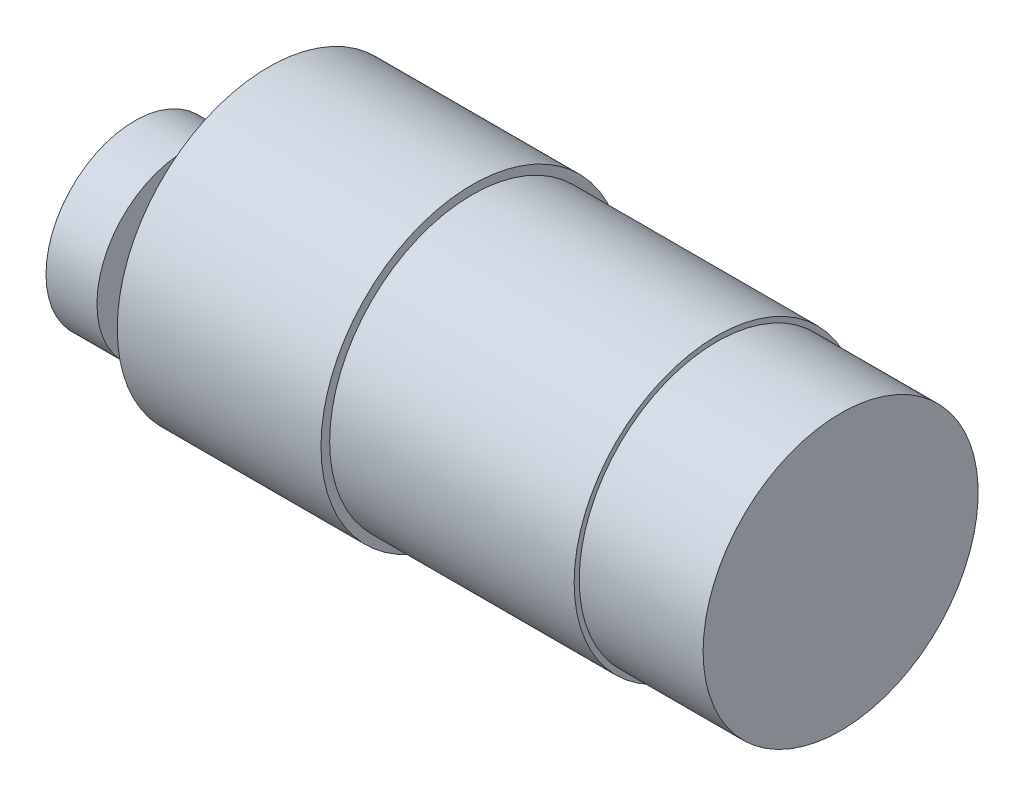
SolidWorks part; units mm, degrees
ref_plane "Face" through (0, 0, 0) normal (0, 0, 1) x (1, 0, 0)
ref_plane "Dessus" through (0, 0, 0) normal (0, 1, 0) x (1, 0, 0)
ref_plane "Droite" through (0, 0, 0) normal (1, 0, 0) x (0, 0, -1)
sketch "Esquisse6" plane through (0, 0, 0) normal (1, 0, 0) x (0, 0, -1)
  circle A0 centre (0, 0) radius 18.8595
  dimension "D1" = 37.719
extrude "Boss.-Extru.2" add sketch "Esquisse6" along normal blind 25.4
sketch "Esquisse7" plane through (25.4, 0, 0) normal (1, 0, 0) x (0, 0, -1)
  circle A0 centre (0, 0) radius 17.78
  dimension "D1" = 35.56
extrude "Boss.-Extru.3" add sketch "Esquisse7" along normal blind 30.48
sketch "Esquisse8" plane through (55.88, 0, 0) normal (1, 0, 0) x (0, 0, -1)
  circle A0 centre (0, 0) radius 17.145
  dimension "D1" = 34.29
extrude "Boss.-Extru.4" add sketch "Esquisse8" along normal blind 15.4432
sketch "Esquisse9" plane through (0, 0, 0) normal (-1, 0, 0) x (0, 0, 1)
  circle A0 centre (0, -6.35) radius 5.969
  dimension "D1" = 11.938
  dimension "D2" = 6.35
extrude "Boss.-Extru.5" add sketch "Esquisse9" along normal blind 6.096
sketch "Esquisse10" plane through (-6.096, 0, 0) normal (-1, 0, 0) x (0, 0, 1)
  circle A0 centre (0, -6.35) radius 4.699
  circle A1 centre (0, -6.35) radius 5.969 construction
  dimension "D1" = 9.398
extrude "Boss.-Extru.6" add sketch "Esquisse10" along normal blind 4.2333
sketch "Esquisse11" plane through (-10.3293, 0, 0) normal (-1, 0, 0) x (0, 0, 1)
  circle A0 centre (0, -6.35) radius 11.0617
  circle A1 centre (0, -6.35) radius 4.699 construction
  dimension "D1" = 22.1234
extrude "Boss.-Extru.7" add sketch "Esquisse11" along normal blind 6.35
sketch "Esquisse12" plane through (-16.6793, 0, 0) normal (-1, 0, 0) x (0, 0, 1)
  circle A0 centre (0, -6.35) radius 4.7752
  circle A1 centre (0, -6.35) radius 11.0617 construction
  dimension "D1" = 9.5504
extrude "Boss.-Extru.8" add sketch "Esquisse12" along normal blind 3.302
hole_wizard "Perçage pour tuyau pour trou taraudé 1/161" positions "Esquisse13" profile "Esquisse15" hole size "1/16" standard "Ansi Inch"
sketch "Esquisse13" plane through (-19.9813, 0, 0) normal (-1, 0, 0) x (0, 0, 1)
  circle A1 centre (0, -6.35) radius 4.7752 construction
  point P0 (0, -6.35)
sketch "Esquisse15" plane through (-19.9813, -6.35, 0) normal (0, 1, 0) x (0, 0, 1)
  line L0 (0, 0) -> (0, 19.9813)
  line L1 (0, 19.9813) -> (3.0734, 19.9813)
  line L2 (3.0734, 19.9813) -> (3.0734, 0)
  line L5 (3.0734, 0) -> (0, 0)
  line L10 (0, 19.9813) -> (-3.0734, 19.9813) construction
  line L11 (0, -6.35) -> (0, 107.95) construction
  dimension "Diamètre du perçage" = 6.1468
  dimension "Profondeur du perçage" = 19.9813
  dimension "Angle de pointe" = 180
sketch "Esquisse16" plane through (0, 0, 0) normal (-1, 0, 0) x (0, 0, 1)
  line L0 (-1.778, -3.9688) -> (1.778, -3.9688)
  arc A0 (-1.778, -3.9688) -> (1.778, -3.9688) centre (0, -6.35) ccw
  point P5 (0, -3.9688)
  dimension "D1" = 5.9436
  dimension "D2" = 3.556
extrude "Boss.-Extru.9" add sketch "Esquisse16" along normal up to surface (19.9813 mm away) up to face at (-19.9813, -6.35, 3.0734)
sketch "Esquisse17" plane through (-19.9813, 0, 0) normal (-1, 0, 0) x (0, 0, 1)
  line L0 (-1.778, -3.9688) -> (1.778, -3.9688)
  arc A3 (-1.778, -3.9688) -> (1.778, -3.9688) centre (0, -6.35) ccw
extrude "Boss.-Extru.10" add sketch "Esquisse17" along normal blind 2.032
sketch "Esquisse18" plane through (-16.6793, 0, 0) normal (-1, 0, 0) x (0, 0, 1)
  circle A1 centre (0, 0.254) radius 1.4605
  circle A3 centre (6.604, -6.35) radius 1.4605
  circle A4 centre (0, -12.954) radius 1.4605
  circle A5 centre (-6.604, -6.35) radius 1.4605
  arc A6 (-1.778, -3.9688) -> (1.778, -3.9688) centre (0, -6.35) ccw construction
  point P15 (0, -6.35)
  dimension "D2" = 2.921
  dimension "D1" = 6.604
  dimension "D5" = 6.604
  dimension "D4" = 6.604
  dimension "D3" = 4
extrude "Enlèv. mat.-Extru.2" cut sketch "Esquisse18" against normal up to next
sketch "Esquisse19" plane through (0, 0, 0) normal (-1, 0, 0) x (0, 0, 1)
  circle A1 centre (6.3762, 14.7894) radius 1.5
  circle A2 centre (7.2533, -15.5106) radius 1.5
  circle A3 centre (-16.8094, 1.555) radius 1.5
  point P12 (0.1484, -0.0315)
  dimension "D1" = 3
  dimension "D3" = 26.6969
  dimension "D2" = 3
  dimension "D4" = 3
  dimension "D5" = 29.5
extrude "Enlèv. mat.-Extru.3" cut sketch "Esquisse19" against normal blind 5
